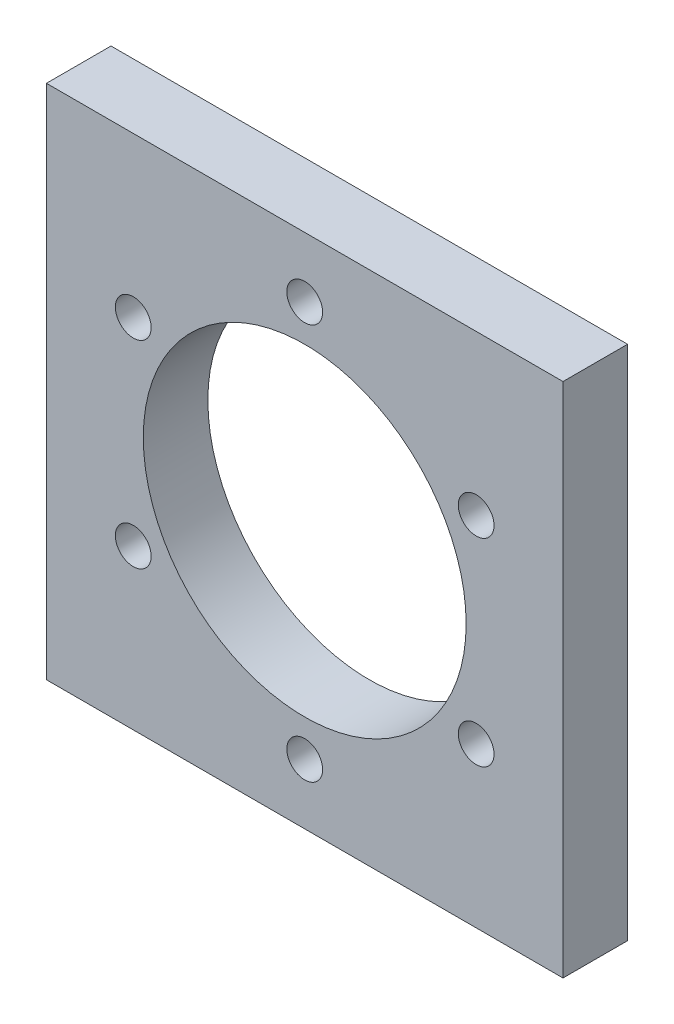
SolidWorks part; units mm, degrees
ref_plane "Front Plane" through (0, 0, 0) normal (0, 0, 1) x (1, 0, 0)
ref_plane "Top Plane" through (0, 0, 0) normal (0, 1, 0) x (1, 0, 0)
ref_plane "Right Plane" through (0, 0, 0) normal (1, 0, 0) x (0, 0, -1)
sketch "Sketch1" plane through (0, 0, 0) normal (0, 0, 1) x (1, 0, 0)
  line L1 (-6.045, 49.495) -> (44.755, 49.495)
  line L2 (-6.045, 49.495) -> (-6.045, -1.305)
  line L3 (-6.045, -1.305) -> (44.755, -1.305)
  line L4 (44.755, 49.495) -> (44.755, -1.305)
  arc A0 (0.7343, 14.3605) -> (4.2543, 14.3605) centre (2.4943, 14.3605) ccw
  arc A1 (4.2543, 14.3605) -> (0.7343, 14.3605) centre (2.4943, 14.3605) ccw
  arc A2 (7.6633, 24.095) -> (31.0467, 24.095) centre (19.355, 24.095) ccw
  arc A3 (31.0467, 24.095) -> (7.6633, 24.095) centre (19.355, 24.095) ccw
  arc A4 (4.2543, 33.8296) -> (0.7343, 33.8296) centre (2.4943, 33.8296) ccw
  arc A5 (0.7343, 33.8296) -> (4.2543, 33.8296) centre (2.4943, 33.8296) ccw
  arc A6 (34.4558, 33.8296) -> (37.9758, 33.8296) centre (36.2158, 33.8296) ccw
  arc A7 (37.9758, 33.8296) -> (34.4558, 33.8296) centre (36.2158, 33.8296) ccw
  arc A8 (21.115, 43.5642) -> (17.595, 43.5642) centre (19.355, 43.5642) ccw
  arc A9 (17.595, 43.5642) -> (21.115, 43.5642) centre (19.355, 43.5642) ccw
  arc A10 (17.595, 4.6259) -> (21.115, 4.6259) centre (19.355, 4.6259) ccw
  arc A11 (21.115, 4.6259) -> (17.595, 4.6259) centre (19.355, 4.6259) ccw
  arc A12 (37.9758, 14.3605) -> (34.4558, 14.3605) centre (36.2158, 14.3605) ccw
  arc A13 (34.4558, 14.3605) -> (37.9758, 14.3605) centre (36.2158, 14.3605) ccw
  circle A14 centre (19.355, 24.095) radius 15.875
  dimension "D5" = 31.75
  dimension "D1" = 25.4
  dimension "D2" = 25.4
  dimension "D3" = 25.4
  dimension "D4" = 25.4
extrude "Boss-Extrude1" add sketch "Sketch1" along normal blind 6.35 contours L4 L1 L2 L3 A14 A13 A12 A11 A10 A9 A8 A7 A6 A5 A4 A1 A0
